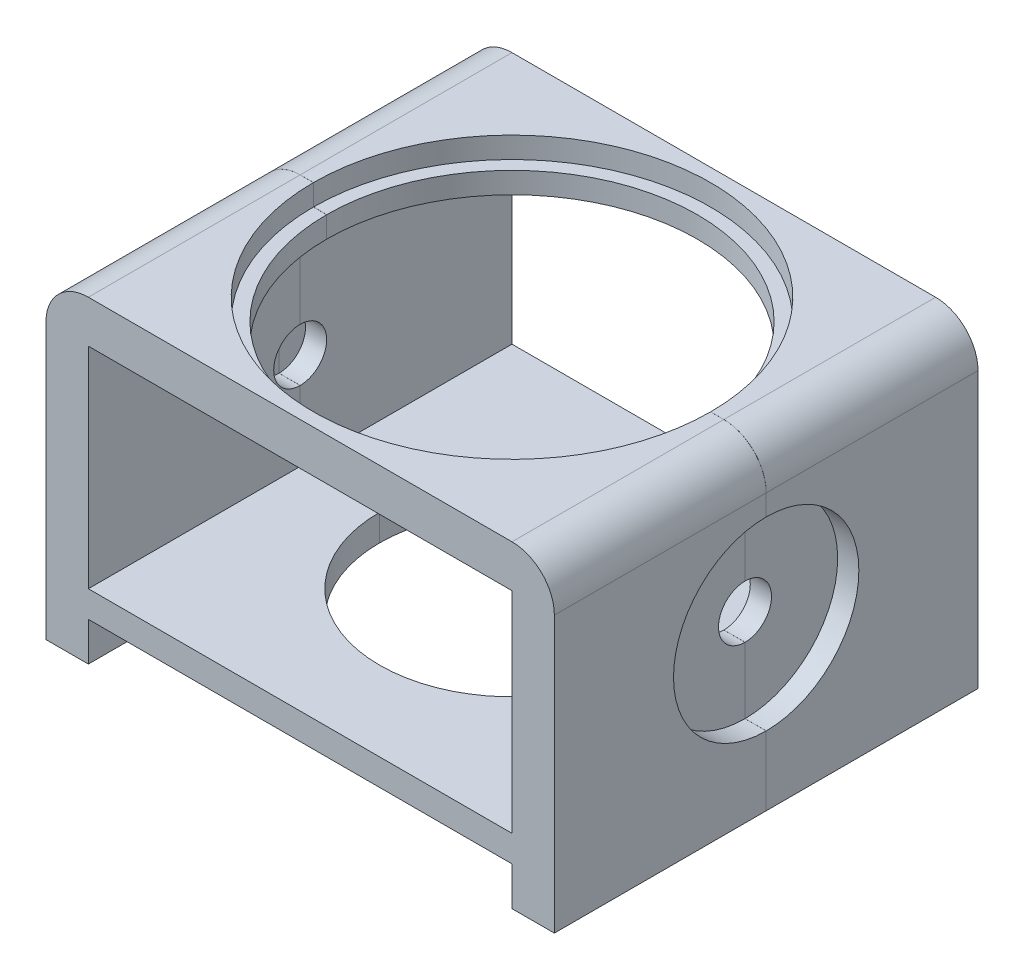
SolidWorks part; units mm, degrees
ref_plane "Front Plane" through (0, 0, 0) normal (0, 0, 1) x (1, 0, 0)
ref_plane "Top Plane" through (0, 0, 0) normal (0, 1, 0) x (1, 0, 0)
ref_plane "Right Plane" through (0, 0, 0) normal (1, 0, 0) x (0, 0, -1)
sketch "Sketch2" plane through (0, 0, 0) normal (0, 0, 1) x (1, 0, 0)
  line L0 (0, 0) -> (0, 52)
  line L1 (-8, 60) -> (-88, 60)
  line L2 (-96, 52) -> (-96, 0)
  line L3 (-96, 0) -> (-88, 0)
  line L4 (-88, 0) -> (-88, 7.3229)
  line L5 (-88, 7.3229) -> (-8, 7.3229)
  line L7 (-8, 12.3229) -> (-88, 12.3229)
  line L8 (-88, 12.3229) -> (-88, 52)
  line L9 (-88, 52) -> (-8, 52)
  line L10 (-8, 52) -> (-8, 12.3229)
  line L11 (-8, 0) -> (0, 0)
  line L12 (-8, 7.3229) -> (-8, 0)
  arc A0 (0, 52) -> (-8, 60) centre (-8, 52) ccw
  arc A1 (-88, 60) -> (-96, 52) centre (-88, 52) ccw
  dimension "D1" = 8
  dimension "D2" = 80
  dimension "D3" = 5
  dimension "D4" = 60
extrude "Boss-Extrude1" add sketch "Sketch2" along normal blind 80
sketch "Sketch3" plane through (0, 60, 0) normal (0, 1, 0) x (1, 0, 0)
  line L0 (-48, 0) -> (-48, -80) construction
  line L1 (-8, 0) -> (-88, 0) construction
  line L2 (-8, -80) -> (-88, -80) construction
  circle A0 centre (-48, -40) radius 37.5
  dimension "D1" = 75
extrude "Cut-Extrude1" cut sketch "Sketch3" against normal blind 4
sketch "Sketch4" plane through (0, 56, 0) normal (0, 1, 0) x (1, 0, 0)
  circle A0 centre (-48, -40) radius 35
  circle A1 centre (-48, -40) radius 37.5 construction
  dimension "D1" = 70
extrude "Cut-Extrude2" cut sketch "Sketch4" against normal blind 4
sketch "Sketch5" plane through (0, 12.3229, 0) normal (0, 1, 0) x (1, 0, 0)
  line L1 (-88, -80) -> (-8, -80) construction
  line L2 (-8, -80) -> (-8, 0) construction
  circle A0 centre (-48, -40) radius 25
  point P6 (-48, -80)
  point P9 (-8, -40)
  dimension "D1" = 50
extrude "Cut-Extrude3" cut sketch "Sketch5" against normal through all
sketch "Sketch6" plane through (0, 12.3229, 0) normal (0, 1, 0) x (1, 0, 0)
  line L0 (-8, -80) -> (-8, 0) construction
  line L1 (-8, -25) -> (-20, -25)
  line L2 (-8, -25) -> (-8, -55)
  line L3 (-8, -55) -> (-20, -55)
  line L4 (-20, -25) -> (-20, -55)
  line L5 (-88, -80) -> (-88, 0) construction
  point P6 (-20, -40)
  point P10 (-88, -40)
  dimension "D1" = 30
  dimension "D2" = 12
extrude "Cut-Extrude4" cut sketch "Sketch6" against normal through all
sketch "Sketch7" plane through (0, 0, 0) normal (1, 0, 0) x (0, 0, -1)
  line L0 (-80, 52) -> (0, 52) construction
  circle A0 centre (-40, 30.57) radius 5
  point P5 (-40, 52)
  dimension "D1" = 10
  dimension "D2" = 21.43
extrude "Cut-Extrude5" cut sketch "Sketch7" against normal offset from surface (92 mm away) 4 up to face at (-96, 26, 40)
sketch "Sketch8" plane through (0, 0, 0) normal (1, 0, 0) x (0, 0, -1)
  circle A0 centre (-40, 30.57) radius 17.5
  dimension "D1" = 35
extrude "Cut-Extrude6" cut sketch "Sketch8" against normal blind 4
ref_plane "Plane1" through (0, 0, 40) normal (0, 0, 1) x (1, 0, 0)
sketch "Sketch9" plane through (0, 0, 40) normal (0, 0, 1) x (1, 0, 0)
  line L1 (-121.5826, 64.6797) -> (31.7642, 64.6797)
  line L2 (-121.5826, 64.6797) -> (-121.5826, -19.6766)
  line L3 (-121.5826, -19.6766) -> (31.7642, -19.6766)
  line L4 (31.7642, 64.6797) -> (31.7642, -19.6766)
extrude "Cut-Extrude8" cut sketch "Sketch9" against normal blind 0.01
split "Split1" bodies to split 111 110 resulting bodies 112 113
